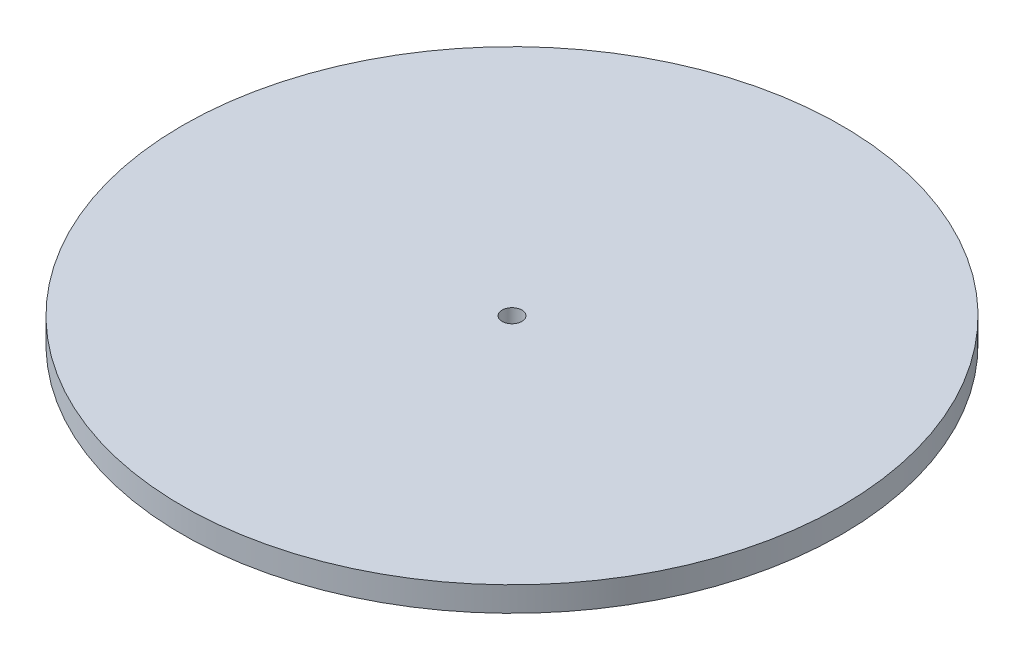
SolidWorks part; units mm, degrees
ref_plane "Front Plane" through (0, 0, 0) normal (0, 0, 1) x (1, 0, 0)
ref_plane "Top Plane" through (0, 0, 0) normal (0, 1, 0) x (1, 0, 0)
ref_plane "Right Plane" through (0, 0, 0) normal (1, 0, 0) x (0, 0, -1)
sketch "Sketch3" plane through (0, 0, 0) normal (0, 0, 1) x (1, 0, 0)
  line L0 (37, 9.0946) -> (37, 13.0946) construction
  line L1 (37, 13.0946) -> (0, 13.0946) construction
  line L2 (0, 13.0946) -> (0, 0) construction
  line L4 (1.2, 13.0946) -> (1.2, 8.0946)
  line L5 (1.2, 8.0946) -> (0, 8.0946)
  line L6 (0, 8.0946) -> (0, 0)
  line L7 (37, 9.0946) -> (40, 9.0946) construction
  line L8 (40, 9.0946) -> (40, 13.0946) construction
  line L9 (40, 13.0946) -> (1.2, 13.0946)
  line L10 (37, 9.0946) -> (37, 10.0946)
  line L11 (37, 10.0946) -> (40, 10.0946)
  line L12 (40, 10.0946) -> (40, 13.0946)
  spline S0 degree 8 poles (-3.7, 0.1603) (1.8433, -0.297) (7.3866, -0.1357) (12.9299, 1.6708) (18.4732, 3.127) (24.0165, 5.0089) (29.5597, 6.7302) (35.103, 8.5151) (40.6463, 10.2353) knots 0 0 0 0 0 0 0 0 0 1 1 1 1 1 1 1 1 1 construction
  spline S1 degree 8 poles (0, 0) (4.625, 0.0014) (9.25, 0.6135) (13.875, 1.9035) (18.5, 3.2275) (23.125, 4.6997) (27.75, 6.1654) (32.375, 7.6392) (37, 9.0946) knots 0.083434 0.083434 0.083434 0.083434 0.083434 0.083434 0.083434 0.083434 0.083434 0.917776 0.917776 0.917776 0.917776 0.917776 0.917776 0.917776 0.917776 0.917776
  dimension "D1" = 3
  dimension "D2" = 1.2
  dimension "D3" = 5
  dimension "D4" = 3
  dimension "D5" = 40
  dimension "D6" = 9.0946
  dimension "D7" = 37
  dimension "D8" = 4
revolve "Revolve4" add sketch "Sketch3" angle 360 about L2
sketch "Sketch5" plane through (0, 13.0946, 0) normal (0, 1, 0) x (1, 0, 0)
  circle A0 centre (0, 0) radius 1.2
  circle A2 centre (0, 0) radius 1.2 construction
extrude "Cut-Extrude1" cut sketch "Sketch5" against normal through all
